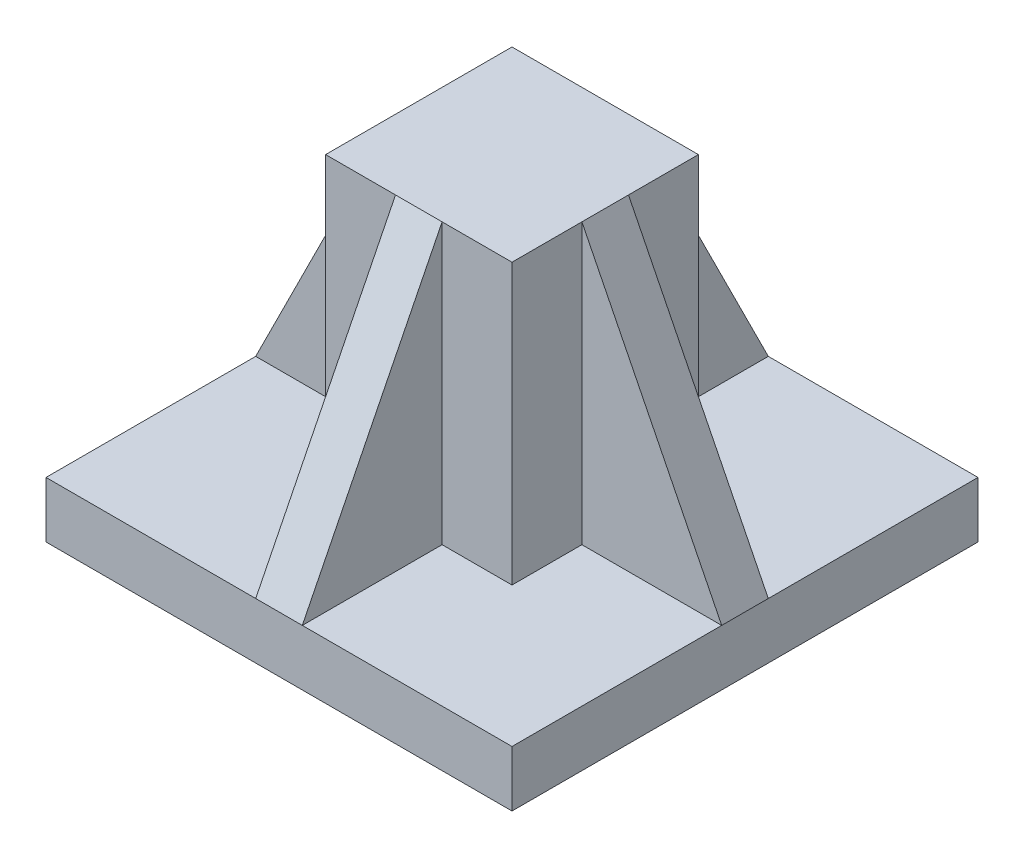
SolidWorks part; units mm, degrees
ref_plane "Front Plane" through (0, 0, 0) normal (0, 0, 1) x (1, 0, 0)
ref_plane "Top Plane" through (0, 0, 0) normal (0, 1, 0) x (1, 0, 0)
ref_plane "Right Plane" through (0, 0, 0) normal (1, 0, 0) x (0, 0, -1)
sketch "Sketch1" plane through (0, 0, 0) normal (0, 1, 0) x (1, 0, 0)
  line L1 (-50, 50) -> (50, 50)
  line L2 (-50, 50) -> (-50, -50)
  line L3 (-50, -50) -> (50, -50)
  line L4 (50, 50) -> (50, -50)
  line L5 (-50, 50) -> (50, -50) construction
  line L6 (-50, -50) -> (50, 50) construction
  point P0 (0, 0)
  dimension "D1" = 100
  dimension "D2" = 100
extrude "Boss-Extrude1" add sketch "Sketch1" along normal blind 12
sketch "Sketch2" plane through (0, 12, 0) normal (0, 1, 0) x (1, 0, 0)
  line L1 (-50, 50) -> (50, 50)
  line L2 (-50, 50) -> (-50, -50)
  line L3 (-50, -50) -> (50, -50)
  line L4 (50, 50) -> (50, -50)
extrude "Boss-Extrude2" add sketch "Sketch2" along normal blind 60 separate body
sketch "Sketch4" plane through (50, 0, 0) normal (1, 0, 0) x (0, 0, -1)
  line L0 (-50, 12) -> (50, 12) construction
  line L1 (-50, 72) -> (-20, 72)
  line L2 (-50, 72) -> (-50, 12)
  line L3 (-50, 12) -> (-20, 12)
  line L4 (-20, 72) -> (-20, 12)
  dimension "D1" = 30
extrude "Cut-Extrude1" cut sketch "Sketch4" against normal blind 45
sketch "Sketch5" plane through (50, 0, 0) normal (1, 0, 0) x (0, 0, -1)
  line L0 (-20, 12) -> (50, 12) construction
  line L1 (50, 72) -> (20, 72)
  line L2 (50, 72) -> (50, 12)
  line L3 (50, 12) -> (20, 12)
  line L4 (20, 72) -> (20, 12)
  dimension "D1" = 30
extrude "Cut-Extrude2" cut sketch "Sketch5" against normal blind 45
ref_plane "Plane3" through (-50, 72, -50) normal (0, 0, 1) x (1, 0, 0)
sketch "Sketch7" plane through (-50, 0, 0) normal (-1, 0, 0) x (0, 0, 1)
  line L0 (-50, 72) -> (50, 72) construction
  line L1 (-50, 12) -> (-20, 12)
  line L2 (-50, 12) -> (-50, 72)
  line L3 (-50, 72) -> (-20, 72)
  line L4 (-20, 12) -> (-20, 72)
  line L5 (-50, 12) -> (50, 12) construction
  line L6 (50, 72) -> (20, 72)
  line L7 (50, 72) -> (50, 12)
  line L8 (50, 12) -> (20, 12)
  line L9 (20, 72) -> (20, 12)
  dimension "D1" = 30
  dimension "D2" = 30
extrude "Cut-Extrude3" cut sketch "Sketch7" against normal blind 45
sketch "Sketch8" plane through (0, 0, 20) normal (0, 0, 1) x (1, 0, 0)
  line L0 (5, 72) -> (50, 72) construction
  line L1 (50, 12) -> (20, 12)
  line L2 (50, 12) -> (50, 72)
  line L3 (50, 72) -> (20, 72)
  line L4 (20, 12) -> (20, 72)
  line L5 (-50, 12) -> (50, 12) construction
  line L6 (-50, 72) -> (-20, 72)
  line L7 (-50, 72) -> (-50, 12)
  line L8 (-50, 12) -> (-20, 12)
  line L9 (-20, 72) -> (-20, 12)
  dimension "D1" = 30
  dimension "D2" = 30
extrude "Cut-Extrude4" cut sketch "Sketch8" against normal blind 15
sketch "Sketch9" plane through (0, 0, -20) normal (0, 0, -1) x (-1, 0, 0)
  line L0 (-50, 12) -> (50, 12) construction
  line L1 (-50, 72) -> (-20, 72)
  line L2 (-50, 72) -> (-50, 12)
  line L3 (-50, 12) -> (-20, 12)
  line L4 (-20, 72) -> (-20, 12)
  line L5 (50, 72) -> (20, 72)
  line L6 (50, 72) -> (50, 12)
  line L7 (50, 12) -> (20, 12)
  line L8 (20, 72) -> (20, 12)
  dimension "D1" = 30
  dimension "D2" = 30
extrude "Cut-Extrude5" cut sketch "Sketch9" against normal blind 15
sketch "Sketch10" plane through (5, 0, 0) normal (1, 0, 0) x (0, 0, -1)
  line L0 (-50, 12) -> (-50, 72)
  line L1 (-50, 72) -> (-20, 72)
  line L2 (-20, 72) -> (-50, 12)
  line L3 (20, 72) -> (50, 12)
  line L4 (50, 12) -> (50, 72)
  line L5 (50, 72) -> (20, 72) construction
  line L6 (50, 12) -> (50, 72) construction
  line L7 (50, 72) -> (20, 72)
extrude "Cut-Extrude6" cut sketch "Sketch10" against normal through all
sketch "Sketch11" plane through (0, 0, 5) normal (0, 0, 1) x (1, 0, 0)
  line L0 (20, 72) -> (50, 72)
  line L1 (50, 72) -> (20, 72) construction
  line L2 (50, 12) -> (50, 72) construction
  line L3 (50, 72) -> (50, 12)
  line L4 (50, 12) -> (20, 72)
  line L5 (-20, 72) -> (-50, 72)
  line L6 (-50, 72) -> (-50, 12)
  line L7 (-50, 12) -> (-20, 72)
extrude "Cut-Extrude7" cut sketch "Sketch11" against normal through all
